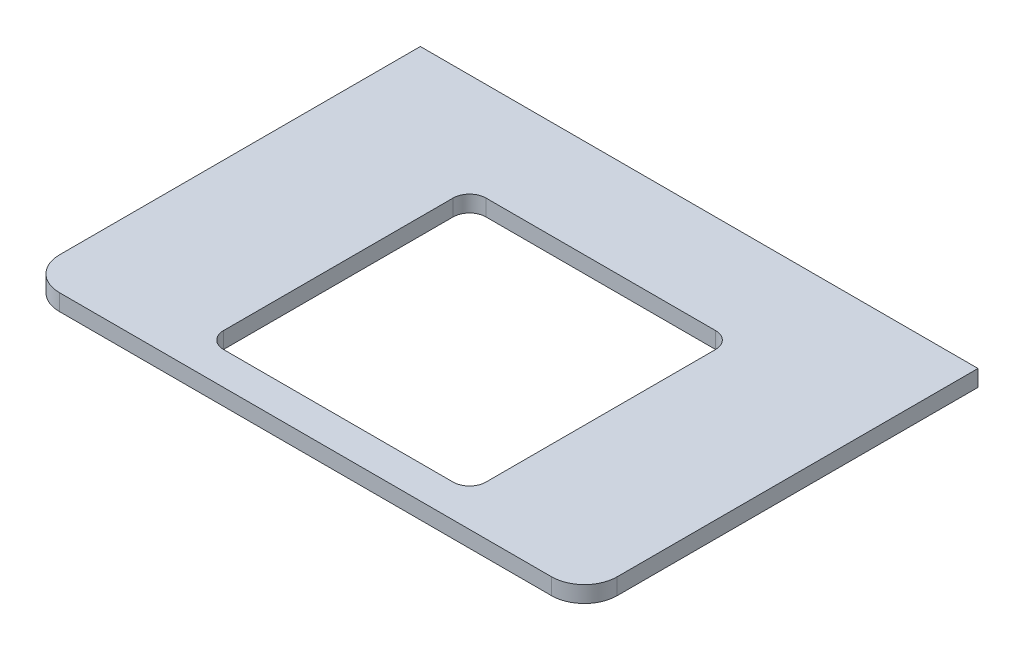
SolidWorks part; units mm, degrees
material "Pin"
ref_plane "Front" through (0, 0, 0) normal (0, 0, 1) x (1, 0, 0)
ref_plane "Top" through (0, 0, 0) normal (0, 1, 0) x (1, 0, 0)
ref_plane "Right" through (0, 0, 0) normal (1, 0, 0) x (0, 0, -1)
sketch "Esquisse1" plane through (0, 0, 0) normal (0, 1, 0) x (1, 0, 0)
  line L1 (-107.95, 76.2) -> (107.95, 76.2)
  line L2 (-107.95, 76.2) -> (-107.95, -76.2)
  line L3 (-107.95, -76.2) -> (107.95, -76.2)
  line L4 (107.95, 76.2) -> (107.95, -76.2)
  line L5 (-107.95, 76.2) -> (107.95, -76.2) construction
  line L6 (-107.95, -76.2) -> (107.95, 76.2) construction
  point P0 (0, 0)
  dimension "D1" = 215.9
  dimension "D2" = 152.4
extrude "Boss.-Extru.1" add sketch "Esquisse1" along normal blind 6.35
fillet "Congé1" radius 12.7 2 edges at (107.95, 3.175, 76.2) (-107.95, 3.175, 76.2)
sketch "Esquisse2" plane through (0, 6.35, 0) normal (0, 1, 0) x (1, 0, 0)
  line L0 (107.95, -63.5) -> (107.95, 76.2) construction
  line L1 (-44.45, 38.1) -> (44.45, 38.1)
  line L2 (-50.8, 31.75) -> (-50.8, -57.15)
  line L3 (-44.45, -63.5) -> (44.45, -63.5)
  line L4 (50.8, 31.75) -> (50.8, -57.15)
  line L5 (-50.8, 38.1) -> (50.8, -63.5) construction
  line L6 (-50.8, -63.5) -> (50.8, 38.1) construction
  line L7 (-95.25, -76.2) -> (95.25, -76.2) construction
  arc A0 (44.45, 38.1) -> (50.8, 31.75) centre (44.45, 31.75) cw
  arc A1 (-44.45, 38.1) -> (-50.8, 31.75) centre (-44.45, 31.75) ccw
  arc A2 (-50.8, -57.15) -> (-44.45, -63.5) centre (-44.45, -57.15) ccw
  arc A3 (44.45, -63.5) -> (50.8, -57.15) centre (44.45, -57.15) ccw
  point P0 (0, -12.7)
  dimension "D5" = 6.35
  dimension "D1" = 101.6
  dimension "D2" = 101.6
  dimension "D3" = 107.95
  dimension "D4" = 63.5
extrude "Enlèv. mat.-Extru.1" cut sketch "Esquisse2" against normal through all
